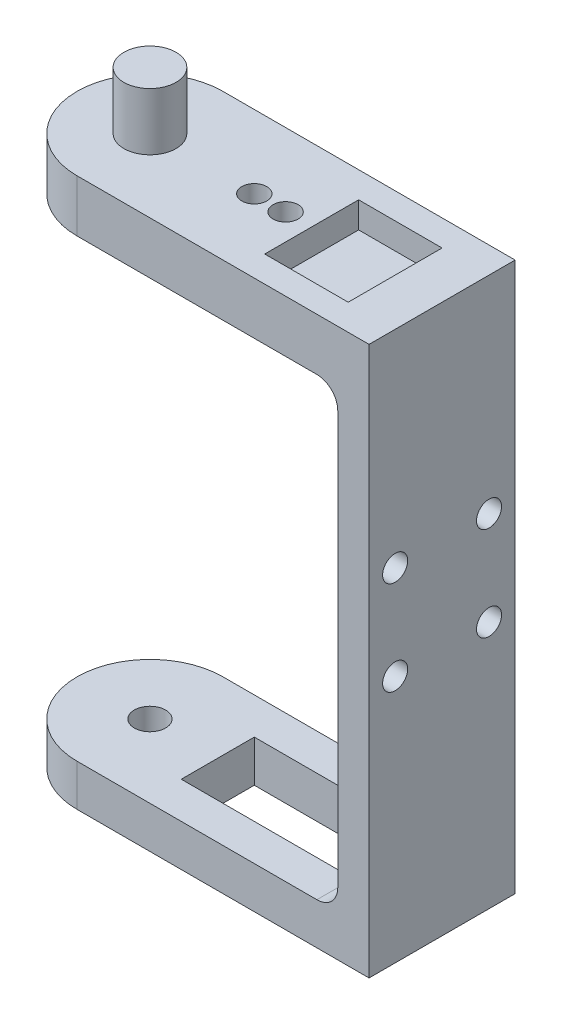
SolidWorks part; units mm, degrees
material "ABS"
ref_plane "Front Plane" through (0, 0, 0) normal (0, 0, 1) x (1, 0, 0)
ref_plane "Top Plane" through (0, 0, 0) normal (0, 1, 0) x (1, 0, 0)
ref_plane "Right Plane" through (0, 0, 0) normal (1, 0, 0) x (0, 0, -1)
ref_plane "Y+19_30" through (0, 19.3, 0) normal (0, 1, 0) x (1, 0, 0)
sketch "Sketch1" plane through (0, 19.3, 0) normal (0, 1, 0) x (1, 0, 0)
  line L0 (5.5, -7) -> (33.5, -7)
  line L1 (33.5, -7) -> (33.5, 7)
  line L2 (33.5, 7) -> (5.5, 7)
  arc A0 (5.5, 7) -> (5.5, -7) centre (5.5, 0) ccw
extrude "Boss-Extrude1" add sketch "Sketch1" along normal blind 5
ref_plane "Y-28_30" through (0, -28.3, 0) normal (0, 1, 0) x (1, 0, 0)
sketch "Sketch2" plane through (0, -28.3, 0) normal (0, 1, 0) x (1, 0, 0)
  line L0 (5.5, -7) -> (33.5, -7)
  line L1 (33.5, -7) -> (33.5, 7)
  line L2 (33.5, 7) -> (5.5, 7)
  arc A0 (5.5, 7) -> (5.5, -7) centre (5.5, 0) ccw
extrude "Boss-Extrude2" add sketch "Sketch2" along normal blind 4
sketch "Sketch3" plane through (0, 0, 0) normal (0, 0, 1) x (1, 0, 0)
  line L0 (7.7, -28.3) -> (-7.7, -28.3) construction
  line L1 (30.5, -28.3) -> (33.5, -28.3)
  line L2 (30.5, -28.3) -> (30.5, 24.3)
  line L3 (30.5, 24.3) -> (33.5, 24.3)
  line L4 (33.5, -28.3) -> (33.5, 24.3)
extrude "Boss-Extrude3" add sketch "Sketch3" along normal mid plane 14
ref_plane "Y+24_30" through (0, 24.3, 0) normal (0, 1, 0) x (1, 0, 0)
sketch "Sketch4" plane through (0, 24.3, 0) normal (0, 1, 0) x (1, 0, 0)
  circle A0 centre (5.5, 0) radius 2.5
extrude "Boss-Extrude4" add sketch "Sketch4" along normal blind 5.5
sketch "Sketch5" plane through (0, 19.3, 0) normal (0, 1, 0) x (1, 0, 0)
  circle A0 centre (5.5, 0) radius 3.7
extrude "Cut-Extrude2" cut sketch "Sketch5" along normal blind 1.6
sketch "Sketch6" plane through (0, 19.3, 0) normal (0, 1, 0) x (1, 0, 0)
  line L0 (5.5, -2.7) -> (20.7, -2.7)
  line L1 (20.7, -2.7) -> (20.7, 2.7)
  line L2 (20.7, 2.7) -> (5.5, 2.7)
  arc A0 (5.5, 2.7) -> (5.5, -2.7) centre (5.5, 0) ccw
extrude "Cut-Extrude4" cut sketch "Sketch6" along normal blind 1.6
ref_plane "Y+20_90" through (0, 20.9, 0) normal (0, 1, 0) x (1, 0, 0)
sketch "Sketch7" plane through (0, 20.9, 0) normal (0, 1, 0) x (1, 0, 0)
  circle A0 centre (5.5, 0) radius 2.5
extrude "Cut-Extrude6" cut sketch "Sketch7" along normal blind 1.6
sketch "Sketch8" plane through (0, -28.3, 0) normal (0, 1, 0) x (1, 0, 0)
  circle A0 centre (5.5, 0) radius 1.5
extrude "Cut-Extrude8" cut sketch "Sketch8" along normal blind 4
hole_wizard "M2 Clearance Hole1" positions "Sketch10" profile "Sketch9" hole size "M2" standard "ISO"
sketch "Sketch10" plane through (0, 24.3, 0) normal (0, 1, 0) x (1, 0, 0)
  point P0 (15.5, 0)
sketch "Sketch9" plane through (15.5, 24.3, 0) normal (1, 0, 0) x (0, 0, 1)
  line L0 (0, 0) -> (0, 5.721)
  line L1 (0, 5.721) -> (1.2, 5)
  line L2 (1.2, 5) -> (1.2, 0)
  line L5 (1.2, 0) -> (0, 0)
  line L10 (0, 5.721) -> (-1.2, 5) construction
  line L11 (0, -6.35) -> (0, 107.95) construction
  dimension "Hole Dia." = 2.4
  dimension "Hole Depth" = 5
  dimension "Drill Angle" = 118
hole_wizard "M2 Clearance Hole2" positions "Sketch12" profile "Sketch11" hole size "M2" standard "ISO"
sketch "Sketch12" plane through (0, 24.3, 0) normal (0, 1, 0) x (1, 0, 0)
  point P0 (18.5, 0)
sketch "Sketch11" plane through (18.5, 24.3, 0) normal (1, 0, 0) x (0, 0, 1)
  line L0 (0, 0) -> (0, 5.721)
  line L1 (0, 5.721) -> (1.2, 5)
  line L2 (1.2, 5) -> (1.2, 0)
  line L5 (1.2, 0) -> (0, 0)
  line L10 (0, 5.721) -> (-1.2, 5) construction
  line L11 (0, -6.35) -> (0, 107.95) construction
  dimension "Hole Dia." = 2.4
  dimension "Hole Depth" = 5
  dimension "Drill Angle" = 118
hole_wizard "M2 Clearance Hole3" positions "Sketch14" profile "Sketch13" hole size "M2" standard "ISO"
sketch "Sketch14" plane through (33.5, 0, 0) normal (1, 0, 0) x (0, 0, -1)
  point P0 (4.5, -4.5)
sketch "Sketch13" plane through (33.5, -4.5, -4.5) normal (0, 1, 0) x (0, 0, -1)
  line L0 (0, 0) -> (0, 35)
  line L1 (0, 35) -> (1.2, 35)
  line L2 (1.2, 35) -> (1.2, 0)
  line L5 (1.2, 0) -> (0, 0)
  line L11 (0, -6.35) -> (0, 107.95) construction
  dimension "Thru Hole Dia." = 2.4
  dimension "Thru Hole Depth" = 35
hole_wizard "M2 Clearance Hole4" positions "Sketch16" profile "Sketch15" hole size "M2" standard "ISO"
sketch "Sketch16" plane through (33.5, 0, 0) normal (1, 0, 0) x (0, 0, -1)
  point P0 (-4.5, -4.5)
sketch "Sketch15" plane through (33.5, -4.5, 4.5) normal (0, 1, 0) x (0, 0, -1)
  line L0 (0, 0) -> (0, 35)
  line L1 (0, 35) -> (1.2, 35)
  line L2 (1.2, 35) -> (1.2, 0)
  line L5 (1.2, 0) -> (0, 0)
  line L11 (0, -6.35) -> (0, 107.95) construction
  dimension "Thru Hole Dia." = 2.4
  dimension "Thru Hole Depth" = 35
hole_wizard "M2 Clearance Hole5" positions "Sketch18" profile "Sketch17" hole size "M2" standard "ISO"
sketch "Sketch18" plane through (33.5, 0, 0) normal (1, 0, 0) x (0, 0, -1)
  point P0 (4.5, 4.5)
sketch "Sketch17" plane through (33.5, 4.5, -4.5) normal (0, 1, 0) x (0, 0, -1)
  line L0 (0, 0) -> (0, 35)
  line L1 (0, 35) -> (1.2, 35)
  line L2 (1.2, 35) -> (1.2, 0)
  line L5 (1.2, 0) -> (0, 0)
  line L11 (0, -6.35) -> (0, 107.95) construction
  dimension "Thru Hole Dia." = 2.4
  dimension "Thru Hole Depth" = 35
hole_wizard "M2 Clearance Hole6" positions "Sketch20" profile "Sketch19" hole size "M2" standard "ISO"
sketch "Sketch20" plane through (33.5, 0, 0) normal (1, 0, 0) x (0, 0, -1)
  point P0 (-4.5, 4.5)
sketch "Sketch19" plane through (33.5, 4.5, 4.5) normal (0, 1, 0) x (0, 0, -1)
  line L0 (0, 0) -> (0, 35)
  line L1 (0, 35) -> (1.2, 35)
  line L2 (1.2, 35) -> (1.2, 0)
  line L5 (1.2, 0) -> (0, 0)
  line L11 (0, -6.35) -> (0, 107.95) construction
  dimension "Thru Hole Dia." = 2.4
  dimension "Thru Hole Depth" = 35
fillet "Fillet1" radius 2 2 edges at (30.5, -24.3, 0) (30.5, 19.3, 0)
sketch "Sketch21" plane through (0, -28.3, 0) normal (0, 1, 0) x (1, 0, 0)
  line L1 (12, -3.5) -> (27, -3.5)
  line L2 (12, -3.5) -> (12, 3.5)
  line L3 (12, 3.5) -> (27, 3.5)
  line L4 (27, -3.5) -> (27, 3.5)
extrude "Cut-Extrude10" cut sketch "Sketch21" along normal blind 4
sketch "Sketch22" plane through (0, 24.3, 0) normal (0, 1, 0) x (1, 0, 0)
  line L1 (21, -4.5) -> (29, -4.5)
  line L2 (21, -4.5) -> (21, 4.5)
  line L3 (21, 4.5) -> (29, 4.5)
  line L4 (29, -4.5) -> (29, 4.5)
extrude "Cut-Extrude11" cut sketch "Sketch22" against normal blind 2.5
